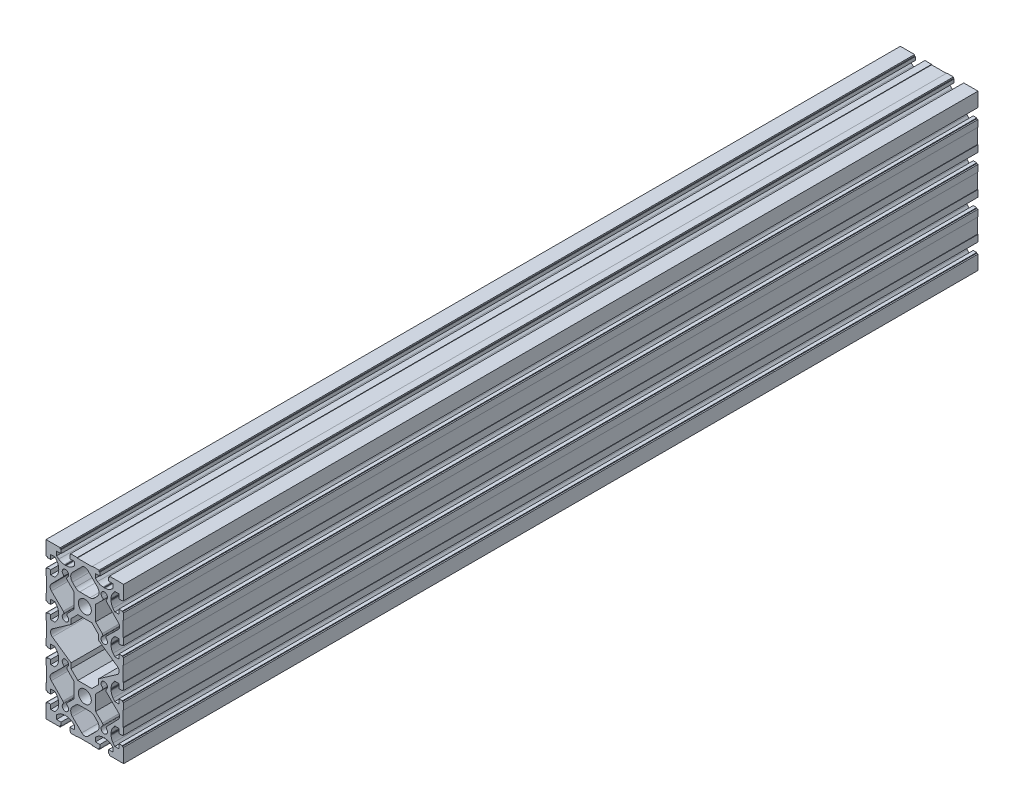
SolidWorks part; units mm, degrees
ref_plane "Front Plane" through (0, 0, 0) normal (0, 0, 1) x (1, 0, 0)
ref_plane "Top Plane" through (0, 0, 0) normal (0, 1, 0) x (1, 0, 0)
ref_plane "Right Plane" through (0, 0, 0) normal (1, 0, 0) x (0, 0, -1)
ref_plane "Plane1" through (0, 0, 10) normal (0, 0, 1) x (1, 0, 0)
sketch "Sketch5" plane through (0, 0, 10) normal (0, 0, 1) x (1, 0, 0)
  line L0 (-45, 36.25) -> (-45, 28.5)
  line L1 (-45, 28.5) -> (-43.5, 28.5)
  line L2 (-43.5, 27.6) -> (-43.5, 28.5)
  line L3 (-39.5, 27.6) -> (-43.5, 27.6)
  line L4 (-39.5, 32.75) -> (-39.5, 27.6)
  line L5 (-34.7299, 32.75) -> (-39.5, 32.75)
  line L6 (-32.713, 30.2467) -> (-34.7299, 32.75)
  line L7 (-30.5, 23) -> (-30.5, 23.9727)
  line L8 (-30, 22.5) -> (-30.5, 23)
  line L9 (-30.5, 22) -> (-30, 22.5)
  line L10 (-30.5, 21.0273) -> (-30.5, 22)
  line L11 (-34.7299, 12.25) -> (-32.713, 14.7533)
  line L12 (-39.5, 12.25) -> (-34.7299, 12.25)
  line L13 (-39.5, 17.4) -> (-39.5, 12.25)
  line L14 (-43.5, 17.4) -> (-39.5, 17.4)
  line L15 (-43.5, 16.5) -> (-43.5, 17.4)
  line L16 (-45, 16.5) -> (-43.5, 16.5)
  line L17 (-45, 16.5) -> (-45, 8.75)
  line L18 (-45, 8.75) -> (-44.5, 8.75)
  line L19 (-44.5, -8.75) -> (-44.5, 8.75)
  line L20 (-45, -8.75) -> (-44.5, -8.75)
  line L21 (-45, -8.75) -> (-45, -16.5)
  line L22 (-45, -16.5) -> (-43.5, -16.5)
  line L23 (-43.5, -17.4) -> (-43.5, -16.5)
  line L24 (-39.5, -17.4) -> (-43.5, -17.4)
  line L25 (-39.5, -12.25) -> (-39.5, -17.4)
  line L26 (-34.7299, -12.25) -> (-39.5, -12.25)
  line L27 (-32.713, -14.7533) -> (-34.7299, -12.25)
  line L28 (-30.5, -22) -> (-30.5, -21.0273)
  line L29 (-30, -22.5) -> (-30.5, -22)
  line L30 (-30.5, -23) -> (-30, -22.5)
  line L31 (-30.5, -23.9727) -> (-30.5, -23)
  line L32 (-34.7299, -32.75) -> (-32.713, -30.2467)
  line L33 (-39.5, -32.75) -> (-34.7299, -32.75)
  line L34 (-39.5, -27.6) -> (-39.5, -32.75)
  line L35 (-43.5, -27.6) -> (-39.5, -27.6)
  line L36 (-43.5, -28.5) -> (-43.5, -27.6)
  line L37 (-45, -28.5) -> (-43.5, -28.5)
  line L38 (-45, -28.5) -> (-45, -36.25)
  line L39 (-45, -36.25) -> (-44.5, -36.25)
  line L40 (-44.5, -53.75) -> (-44.5, -36.25)
  line L41 (-45, -53.75) -> (-44.5, -53.75)
  line L42 (-45, -53.75) -> (-45, -61.5)
  line L43 (-45, -61.5) -> (-43.5, -61.5)
  line L44 (-43.5, -62.4) -> (-43.5, -61.5)
  line L45 (-39.5, -62.4) -> (-43.5, -62.4)
  line L46 (-39.5, -57.25) -> (-39.5, -62.4)
  line L47 (-34.7299, -57.25) -> (-39.5, -57.25)
  line L48 (-32.713, -59.7533) -> (-34.7299, -57.25)
  line L49 (-30.5, -67) -> (-30.5, -66.0273)
  line L50 (-30, -67.5) -> (-30.5, -67)
  line L51 (-30.5, -68) -> (-30, -67.5)
  line L52 (-30.5, -68.9727) -> (-30.5, -68)
  line L53 (-34.7299, -77.75) -> (-32.713, -75.2467)
  line L54 (-39.5, -77.75) -> (-34.7299, -77.75)
  line L55 (-39.5, -72.6) -> (-39.5, -77.75)
  line L56 (-43.5, -72.6) -> (-39.5, -72.6)
  line L57 (-43.5, -73.5) -> (-43.5, -72.6)
  line L58 (-45, -73.5) -> (-43.5, -73.5)
  line L59 (-45, -73.5) -> (-45, -90)
  line L60 (-45, -90) -> (-28.5, -90)
  line L61 (-28.5, -90) -> (-28.5, -88.5)
  line L62 (-27.6, -88.5) -> (-28.5, -88.5)
  line L63 (-27.6, -84.5) -> (-27.6, -88.5)
  line L64 (-32.75, -84.5) -> (-27.6, -84.5)
  line L65 (-32.75, -79.7299) -> (-32.75, -84.5)
  line L66 (-30.2467, -77.713) -> (-32.75, -79.7299)
  line L67 (-23, -75.5) -> (-23.9727, -75.5)
  line L68 (-22.5, -75) -> (-23, -75.5)
  line L69 (-22, -75.5) -> (-22.5, -75)
  line L70 (-21.0273, -75.5) -> (-22, -75.5)
  line L71 (-12.25, -79.7299) -> (-14.7533, -77.713)
  line L72 (-12.25, -84.5) -> (-12.25, -79.7299)
  line L73 (-17.4, -84.5) -> (-12.25, -84.5)
  line L74 (-17.4, -88.5) -> (-17.4, -84.5)
  line L75 (-16.5, -88.5) -> (-17.4, -88.5)
  line L76 (-16.5, -90) -> (-16.5, -88.5)
  line L77 (-16.5, -90) -> (-8.75, -90)
  line L78 (-8.75, -90) -> (-8.75, -89.5)
  line L79 (8.75, -89.5) -> (-8.75, -89.5)
  line L80 (8.75, -90) -> (8.75, -89.5)
  line L81 (8.75, -90) -> (16.5, -90)
  line L82 (16.5, -90) -> (16.5, -88.5)
  line L83 (17.4, -88.5) -> (16.5, -88.5)
  line L84 (17.4, -84.5) -> (17.4, -88.5)
  line L85 (12.25, -84.5) -> (17.4, -84.5)
  line L86 (12.25, -79.7299) -> (12.25, -84.5)
  line L87 (14.7533, -77.713) -> (12.25, -79.7299)
  line L88 (22, -75.5) -> (21.0273, -75.5)
  line L89 (22.5, -75) -> (22, -75.5)
  line L90 (23, -75.5) -> (22.5, -75)
  line L91 (23.9727, -75.5) -> (23, -75.5)
  line L92 (32.75, -79.7299) -> (30.2467, -77.713)
  line L93 (32.75, -84.5) -> (32.75, -79.7299)
  line L94 (27.6, -84.5) -> (32.75, -84.5)
  line L95 (27.6, -88.5) -> (27.6, -84.5)
  line L96 (28.5, -88.5) -> (27.6, -88.5)
  line L97 (28.5, -90) -> (28.5, -88.5)
  line L98 (28.5, -90) -> (45, -90)
  line L99 (45, -90) -> (45, -73.5)
  line L100 (45, -73.5) -> (43.5, -73.5)
  line L101 (43.5, -72.6) -> (43.5, -73.5)
  line L102 (39.5, -72.6) -> (43.5, -72.6)
  line L103 (39.5, -77.75) -> (39.5, -72.6)
  line L104 (34.7299, -77.75) -> (39.5, -77.75)
  line L105 (32.713, -75.2467) -> (34.7299, -77.75)
  line L106 (30.5, -68) -> (30.5, -68.9727)
  line L107 (30, -67.5) -> (30.5, -68)
  line L108 (30.5, -67) -> (30, -67.5)
  line L109 (30.5, -66.0273) -> (30.5, -67)
  line L110 (34.7299, -57.25) -> (32.713, -59.7533)
  line L111 (39.5, -57.25) -> (34.7299, -57.25)
  line L112 (39.5, -62.4) -> (39.5, -57.25)
  line L113 (43.5, -62.4) -> (39.5, -62.4)
  line L114 (43.5, -61.5) -> (43.5, -62.4)
  line L115 (45, -61.5) -> (43.5, -61.5)
  line L116 (45, -61.5) -> (45, -53.75)
  line L117 (45, -53.75) -> (44.5, -53.75)
  line L118 (44.5, -36.25) -> (44.5, -53.75)
  line L119 (45, -36.25) -> (44.5, -36.25)
  line L120 (45, -36.25) -> (45, -28.5)
  line L121 (45, -28.5) -> (43.5, -28.5)
  line L122 (43.5, -27.6) -> (43.5, -28.5)
  line L123 (39.5, -27.6) -> (43.5, -27.6)
  line L124 (39.5, -32.75) -> (39.5, -27.6)
  line L125 (34.7299, -32.75) -> (39.5, -32.75)
  line L126 (32.713, -30.2467) -> (34.7299, -32.75)
  line L127 (30.5, -23) -> (30.5, -23.9727)
  line L128 (30, -22.5) -> (30.5, -23)
  line L129 (30.5, -22) -> (30, -22.5)
  line L130 (30.5, -21.0273) -> (30.5, -22)
  line L131 (34.7299, -12.25) -> (32.713, -14.7533)
  line L132 (39.5, -12.25) -> (34.7299, -12.25)
  line L133 (39.5, -17.4) -> (39.5, -12.25)
  line L134 (43.5, -17.4) -> (39.5, -17.4)
  line L135 (43.5, -16.5) -> (43.5, -17.4)
  line L136 (45, -16.5) -> (43.5, -16.5)
  line L137 (45, -16.5) -> (45, -8.75)
  line L138 (45, -8.75) -> (44.5, -8.75)
  line L139 (44.5, 8.75) -> (44.5, -8.75)
  line L140 (45, 8.75) -> (44.5, 8.75)
  line L141 (45, 8.75) -> (45, 16.5)
  line L142 (45, 16.5) -> (43.5, 16.5)
  line L143 (43.5, 17.4) -> (43.5, 16.5)
  line L144 (39.5, 17.4) -> (43.5, 17.4)
  line L145 (39.5, 12.25) -> (39.5, 17.4)
  line L146 (34.7299, 12.25) -> (39.5, 12.25)
  line L147 (32.713, 14.7533) -> (34.7299, 12.25)
  line L148 (30.5, 22) -> (30.5, 21.0273)
  line L149 (30, 22.5) -> (30.5, 22)
  line L150 (30.5, 23) -> (30, 22.5)
  line L151 (30.5, 23.9727) -> (30.5, 23)
  line L152 (34.7299, 32.75) -> (32.713, 30.2467)
  line L153 (39.5, 32.75) -> (34.7299, 32.75)
  line L154 (39.5, 27.6) -> (39.5, 32.75)
  line L155 (43.5, 27.6) -> (39.5, 27.6)
  line L156 (43.5, 28.5) -> (43.5, 27.6)
  line L157 (45, 28.5) -> (43.5, 28.5)
  line L158 (45, 28.5) -> (45, 36.25)
  line L159 (45, 36.25) -> (44.5, 36.25)
  line L160 (44.5, 53.75) -> (44.5, 36.25)
  line L161 (45, 53.75) -> (44.5, 53.75)
  line L162 (45, 53.75) -> (45, 61.5)
  line L163 (45, 61.5) -> (43.5, 61.5)
  line L164 (43.5, 62.4) -> (43.5, 61.5)
  line L165 (39.5, 62.4) -> (43.5, 62.4)
  line L166 (39.5, 57.25) -> (39.5, 62.4)
  line L167 (34.7299, 57.25) -> (39.5, 57.25)
  line L168 (32.713, 59.7533) -> (34.7299, 57.25)
  line L169 (30.5, 67) -> (30.5, 66.0273)
  line L170 (30, 67.5) -> (30.5, 67)
  line L171 (30.5, 68) -> (30, 67.5)
  line L172 (30.5, 68.9727) -> (30.5, 68)
  line L173 (34.7299, 77.75) -> (32.713, 75.2467)
  line L174 (39.5, 77.75) -> (34.7299, 77.75)
  line L175 (39.5, 72.6) -> (39.5, 77.75)
  line L176 (43.5, 72.6) -> (39.5, 72.6)
  line L177 (43.5, 73.5) -> (43.5, 72.6)
  line L178 (45, 73.5) -> (43.5, 73.5)
  line L179 (45, 73.5) -> (45, 90)
  line L180 (45, 90) -> (28.5, 90)
  line L181 (28.5, 90) -> (28.5, 88.5)
  line L182 (27.6, 88.5) -> (28.5, 88.5)
  line L183 (27.6, 84.5) -> (27.6, 88.5)
  line L184 (32.75, 84.5) -> (27.6, 84.5)
  line L185 (32.75, 79.7299) -> (32.75, 84.5)
  line L186 (30.2467, 77.713) -> (32.75, 79.7299)
  line L187 (23, 75.5) -> (23.9727, 75.5)
  line L188 (22.5, 75) -> (23, 75.5)
  line L189 (22, 75.5) -> (22.5, 75)
  line L190 (21.0273, 75.5) -> (22, 75.5)
  line L191 (12.25, 79.7299) -> (14.7533, 77.713)
  line L192 (12.25, 84.5) -> (12.25, 79.7299)
  line L193 (17.4, 84.5) -> (12.25, 84.5)
  line L194 (17.4, 88.5) -> (17.4, 84.5)
  line L195 (16.5, 88.5) -> (17.4, 88.5)
  line L196 (16.5, 90) -> (16.5, 88.5)
  line L197 (16.5, 90) -> (8.75, 90)
  line L198 (8.75, 90) -> (8.75, 89.5)
  line L199 (-8.75, 89.5) -> (8.75, 89.5)
  line L200 (-8.75, 90) -> (-8.75, 89.5)
  line L201 (-8.75, 90) -> (-16.5, 90)
  line L202 (-16.5, 90) -> (-16.5, 88.5)
  line L203 (-17.4, 88.5) -> (-16.5, 88.5)
  line L204 (-17.4, 84.5) -> (-17.4, 88.5)
  line L205 (-12.25, 84.5) -> (-17.4, 84.5)
  line L206 (-12.25, 79.7299) -> (-12.25, 84.5)
  line L207 (-14.7533, 77.713) -> (-12.25, 79.7299)
  line L208 (-22, 75.5) -> (-21.0273, 75.5)
  line L209 (-22.5, 75) -> (-22, 75.5)
  line L210 (-23, 75.5) -> (-22.5, 75)
  line L211 (-23.9727, 75.5) -> (-23, 75.5)
  line L212 (-32.75, 79.7299) -> (-30.2467, 77.713)
  line L213 (-32.75, 84.5) -> (-32.75, 79.7299)
  line L214 (-27.6, 84.5) -> (-32.75, 84.5)
  line L215 (-27.6, 88.5) -> (-27.6, 84.5)
  line L216 (-28.5, 88.5) -> (-27.6, 88.5)
  line L217 (-28.5, 90) -> (-28.5, 88.5)
  line L218 (-28.5, 90) -> (-45, 90)
  line L219 (-45, 90) -> (-45, 73.5)
  line L220 (-45, 73.5) -> (-43.5, 73.5)
  line L221 (-43.5, 72.6) -> (-43.5, 73.5)
  line L222 (-39.5, 72.6) -> (-43.5, 72.6)
  line L223 (-39.5, 77.75) -> (-39.5, 72.6)
  line L224 (-34.7299, 77.75) -> (-39.5, 77.75)
  line L225 (-32.713, 75.2467) -> (-34.7299, 77.75)
  line L226 (-30.5, 68) -> (-30.5, 68.9727)
  line L227 (-30, 67.5) -> (-30.5, 68)
  line L228 (-30.5, 67) -> (-30, 67.5)
  line L229 (-30.5, 66.0273) -> (-30.5, 67)
  line L230 (-34.7299, 57.25) -> (-32.713, 59.7533)
  line L231 (-39.5, 57.25) -> (-34.7299, 57.25)
  line L232 (-39.5, 62.4) -> (-39.5, 57.25)
  line L233 (-43.5, 62.4) -> (-39.5, 62.4)
  line L234 (-43.5, 61.5) -> (-43.5, 62.4)
  line L235 (-45, 61.5) -> (-43.5, 61.5)
  line L236 (-45, 61.5) -> (-45, 53.75)
  line L237 (-45, 53.75) -> (-44.5, 53.75)
  line L238 (-44.5, 36.25) -> (-44.5, 53.75)
  line L239 (-45, 36.25) -> (-44.5, 36.25)
  line L240 (-14.3511, 62.5665) -> (-10.8598, 59.0634)
  line L241 (-3.5415, 83.2796) -> (-14.3511, 72.4335)
  line L242 (14.3511, 72.4335) -> (3.5415, 83.2796)
  line L243 (10.8598, 59.0634) -> (14.3511, 62.5665)
  line L244 (-5.9097, 57.0081) -> (5.9097, 57.0081)
  line L245 (5.9097, -57.0081) -> (-5.9097, -57.0081)
  line L246 (14.3511, -62.5665) -> (10.8598, -59.0634)
  line L247 (3.5415, -83.2796) -> (14.3511, -72.4335)
  line L248 (-14.3511, -72.4335) -> (-3.5415, -83.2796)
  line L249 (-10.8598, -59.0634) -> (-14.3511, -62.5665)
  line L250 (-16, -25.11) -> (-8.11, -33)
  line L251 (-16, -19.23) -> (-16, -25.11)
  line L252 (-37.6117, -4.0956) -> (-16, -19.23)
  line L253 (-16, 19.23) -> (-37.6117, 4.0956)
  line L254 (-16, 25.11) -> (-16, 19.23)
  line L255 (-8.11, 33) -> (-16, 25.11)
  line L256 (8.11, 33) -> (-8.11, 33)
  line L257 (16, 25.11) -> (8.11, 33)
  line L258 (16, 19.23) -> (16, 25.11)
  line L259 (37.6117, 4.0956) -> (16, 19.23)
  line L260 (16, -19.23) -> (37.6117, -4.0956)
  line L261 (16, -25.11) -> (16, -19.23)
  line L262 (8.11, -33) -> (16, -25.11)
  line L263 (-8.11, -33) -> (8.11, -33)
  line L264 (38.8162, 48.5787) -> (25.3686, 62.3609)
  line L265 (24.9895, 28.1019) -> (38.7293, 41.5082)
  line L266 (12.49, 36.185) -> (20.2409, 28.2413)
  line L267 (12.49, 53.815) -> (12.49, 36.185)
  line L268 (20.4192, 61.5517) -> (12.49, 53.815)
  line L269 (-12.49, 53.815) -> (-20.4192, 61.5517)
  line L270 (-12.49, 36.185) -> (-12.49, 53.815)
  line L271 (-20.2409, 28.2413) -> (-12.49, 36.185)
  line L272 (-38.7293, 41.5082) -> (-24.9895, 28.1019)
  line L273 (-25.3686, 62.3609) -> (-38.8162, 48.5787)
  line L274 (12.49, -53.815) -> (20.4192, -61.5517)
  line L275 (12.49, -36.185) -> (12.49, -53.815)
  line L276 (20.2409, -28.2413) -> (12.49, -36.185)
  line L277 (38.7293, -41.5082) -> (24.9895, -28.1019)
  line L278 (25.3686, -62.3609) -> (38.8162, -48.5787)
  line L279 (-38.8162, -48.5787) -> (-25.3686, -62.3609)
  line L280 (-24.9895, -28.1019) -> (-38.7293, -41.5082)
  line L281 (-12.49, -36.185) -> (-20.2409, -28.2413)
  line L282 (-12.49, -53.815) -> (-12.49, -36.185)
  line L283 (-20.4192, -61.5517) -> (-12.49, -53.815)
  arc A0 (-30.5, 23.9727) -> (-32.713, 30.2467) centre (-40.5, 23.9727) ccw
  arc A1 (-32.713, 14.7533) -> (-30.5, 21.0273) centre (-40.5, 21.0273) ccw
  arc A2 (-30.5, -21.0273) -> (-32.713, -14.7533) centre (-40.5, -21.0273) ccw
  arc A3 (-32.713, -30.2467) -> (-30.5, -23.9727) centre (-40.5, -23.9727) ccw
  arc A4 (-30.5, -66.0273) -> (-32.713, -59.7533) centre (-40.5, -66.0273) ccw
  arc A5 (-32.713, -75.2467) -> (-30.5, -68.9727) centre (-40.5, -68.9727) ccw
  arc A6 (-23.9727, -75.5) -> (-30.2467, -77.713) centre (-23.9727, -85.5) ccw
  arc A7 (-14.7533, -77.713) -> (-21.0273, -75.5) centre (-21.0273, -85.5) ccw
  arc A8 (21.0273, -75.5) -> (14.7533, -77.713) centre (21.0273, -85.5) ccw
  arc A9 (30.2467, -77.713) -> (23.9727, -75.5) centre (23.9727, -85.5) ccw
  arc A10 (30.5, -68.9727) -> (32.713, -75.2467) centre (40.5, -68.9727) ccw
  arc A11 (32.713, -59.7533) -> (30.5, -66.0273) centre (40.5, -66.0273) ccw
  arc A12 (30.5, -23.9727) -> (32.713, -30.2467) centre (40.5, -23.9727) ccw
  arc A13 (32.713, -14.7533) -> (30.5, -21.0273) centre (40.5, -21.0273) ccw
  arc A14 (30.5, 21.0273) -> (32.713, 14.7533) centre (40.5, 21.0273) ccw
  arc A15 (32.713, 30.2467) -> (30.5, 23.9727) centre (40.5, 23.9727) ccw
  arc A16 (30.5, 66.0273) -> (32.713, 59.7533) centre (40.5, 66.0273) ccw
  arc A17 (32.713, 75.2467) -> (30.5, 68.9727) centre (40.5, 68.9727) ccw
  arc A18 (23.9727, 75.5) -> (30.2467, 77.713) centre (23.9727, 85.5) ccw
  arc A19 (14.7533, 77.713) -> (21.0273, 75.5) centre (21.0273, 85.5) ccw
  arc A20 (-21.0273, 75.5) -> (-14.7533, 77.713) centre (-21.0273, 85.5) ccw
  arc A21 (-30.2467, 77.713) -> (-23.9727, 75.5) centre (-23.9727, 85.5) ccw
  arc A22 (-30.5, 68.9727) -> (-32.713, 75.2467) centre (-40.5, 68.9727) ccw
  arc A23 (-32.713, 59.7533) -> (-30.5, 66.0273) centre (-40.5, 66.0273) ccw
  circle A24 centre (0, 45.0869) radius 7.5
  circle A25 centre (0, -45.0869) radius 7.5
  arc A26 (-10.8598, 59.0634) -> (-5.9097, 57.0081) centre (-5.9097, 63.997) ccw
  arc A27 (-14.3511, 72.4335) -> (-14.3511, 62.5665) centre (-9.4009, 67.5) ccw
  arc A28 (3.5415, 83.2796) -> (-3.5415, 83.2796) centre (0, 79.75) ccw
  arc A29 (14.3511, 62.5665) -> (14.3511, 72.4335) centre (9.4009, 67.5) ccw
  arc A30 (5.9097, 57.0081) -> (10.8598, 59.0634) centre (5.9097, 63.997) ccw
  arc A31 (10.8598, -59.0634) -> (5.9097, -57.0081) centre (5.9097, -63.997) ccw
  arc A32 (14.3511, -72.4335) -> (14.3511, -62.5665) centre (9.4009, -67.5) ccw
  arc A33 (-3.5415, -83.2796) -> (3.5415, -83.2796) centre (0, -79.75) ccw
  arc A34 (-14.3511, -62.5665) -> (-14.3511, -72.4335) centre (-9.4009, -67.5) ccw
  arc A35 (-5.9097, -57.0081) -> (-10.8598, -59.0634) centre (-5.9097, -63.997) ccw
  arc A36 (-37.6117, 4.0956) -> (-37.6117, -4.0956) centre (-34.7436, 0) ccw
  arc A37 (37.6117, -4.0956) -> (37.6117, 4.0956) centre (34.7436, 0) ccw
  arc A38 (38.7293, 41.5082) -> (38.8162, 48.5787) centre (35.2375, 45.0869) ccw
  arc A39 (24.9895, 28.1019) -> (25.0228, 25.2073) centre (26.3862, 26.6705) ccw
  arc A40 (20.1042, 25.3203) -> (25.0228, 25.2073) centre (22.5, 22.5) ccw
  arc A41 (20.1042, 25.3203) -> (20.2409, 28.2413) centre (18.8094, 26.8445) ccw
  arc A42 (20.4192, 61.5517) -> (20.2425, 64.5679) centre (19.0224, 62.9831) ccw
  arc A43 (25.2914, 65.0706) -> (20.2425, 64.5679) centre (22.5, 67.5) ccw
  arc A44 (25.2914, 65.0706) -> (25.3686, 62.3609) centre (26.8, 63.7577) ccw
  arc A45 (-25.3686, 62.3609) -> (-25.2914, 65.0706) centre (-26.8, 63.7577) ccw
  arc A46 (-20.2425, 64.5679) -> (-25.2914, 65.0706) centre (-22.5, 67.5) ccw
  arc A47 (-20.2425, 64.5679) -> (-20.4192, 61.5517) centre (-19.0224, 62.9831) ccw
  arc A48 (-20.2409, 28.2413) -> (-20.1042, 25.3203) centre (-18.8094, 26.8445) ccw
  arc A49 (-25.0228, 25.2073) -> (-20.1042, 25.3203) centre (-22.5, 22.5) ccw
  arc A50 (-25.0228, 25.2073) -> (-24.9895, 28.1019) centre (-26.3862, 26.6705) ccw
  arc A51 (-38.8162, 48.5787) -> (-38.7293, 41.5082) centre (-35.2375, 45.0869) ccw
  arc A52 (25.3686, -62.3609) -> (25.2914, -65.0706) centre (26.8, -63.7577) ccw
  arc A53 (20.2425, -64.5679) -> (25.2914, -65.0706) centre (22.5, -67.5) ccw
  arc A54 (20.2425, -64.5679) -> (20.4192, -61.5517) centre (19.0224, -62.9831) ccw
  arc A55 (20.2409, -28.2413) -> (20.1042, -25.3203) centre (18.8094, -26.8445) ccw
  arc A56 (25.0228, -25.2073) -> (20.1042, -25.3203) centre (22.5, -22.5) ccw
  arc A57 (25.0228, -25.2073) -> (24.9895, -28.1019) centre (26.3862, -26.6705) ccw
  arc A58 (38.8162, -48.5787) -> (38.7293, -41.5082) centre (35.2375, -45.0869) ccw
  arc A59 (-38.7293, -41.5082) -> (-38.8162, -48.5787) centre (-35.2375, -45.0869) ccw
  arc A60 (-24.9895, -28.1019) -> (-25.0228, -25.2073) centre (-26.3862, -26.6705) ccw
  arc A61 (-20.1042, -25.3203) -> (-25.0228, -25.2073) centre (-22.5, -22.5) ccw
  arc A62 (-20.1042, -25.3203) -> (-20.2409, -28.2413) centre (-18.8094, -26.8445) ccw
  arc A63 (-20.4192, -61.5517) -> (-20.2425, -64.5679) centre (-19.0224, -62.9831) ccw
  arc A64 (-25.2914, -65.0706) -> (-20.2425, -64.5679) centre (-22.5, -67.5) ccw
  arc A65 (-25.2914, -65.0706) -> (-25.3686, -62.3609) centre (-26.8, -63.7577) ccw
  point P76 (0, 0)
  point P77 (-45, 81.75)
  dimension "D1" = 15
  dimension "D2" = 15
  dimension "D3" = 45
  dimension "D4" = 180
  dimension "D5" = 90
  dimension "D6" = 22.5
  dimension "D7" = 67.5
extrude "Boss-Extrude1" add sketch "Sketch5" along normal blind 990
equation "\"Lx_Alu_profile_90x180_Tuli\"= 990"
equation "\"D1@Boss-Extrude1\"=\"Lx_Alu_profile_90x180_Tuli\""
